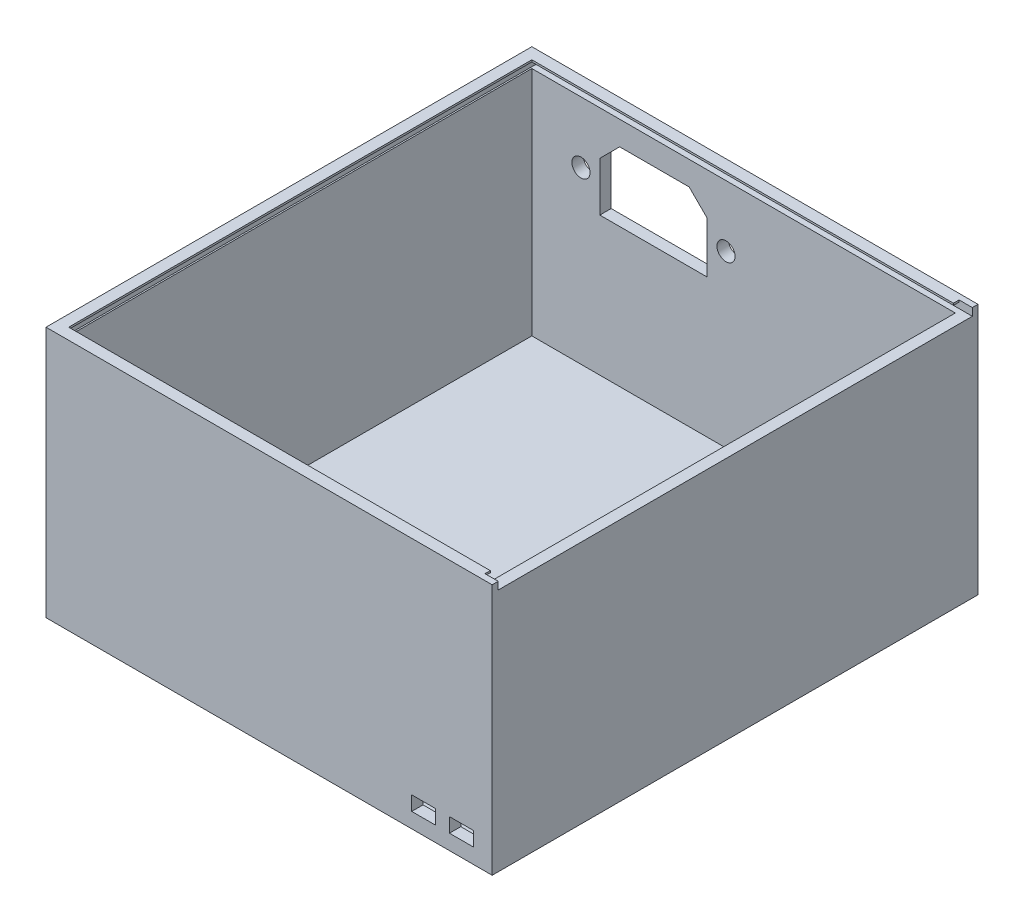
SolidWorks part; units mm, degrees
ref_plane "Front Plane" through (0, 0, 0) normal (0, 0, 1) x (1, 0, 0)
ref_plane "Top Plane" through (0, 0, 0) normal (0, 1, 0) x (1, 0, 0)
ref_plane "Right Plane" through (0, 0, 0) normal (1, 0, 0) x (0, 0, -1)
sketch "Sketch1" plane through (0, 0, 0) normal (0, 1, 0) x (1, 0, 0)
  line L1 (-59.05, 64.3) -> (59.05, 64.3)
  line L2 (-59.05, 64.3) -> (-59.05, -64.3)
  line L3 (-59.05, -64.3) -> (59.05, -64.3)
  line L4 (59.05, 64.3) -> (59.05, -64.3)
  line L5 (-59.05, 64.3) -> (59.05, -64.3) construction
  line L6 (-59.05, -64.3) -> (59.05, 64.3) construction
  point P0 (0, 0)
  dimension "D1" = 118.1
  dimension "D2" = 128.6
extrude "Boss-Extrude2" add sketch "Sketch1" along normal blind 66.6
sketch "Sketch4" plane through (0, 0, 64.3) normal (0, 0, 1) x (1, 0, 0)
  line L0 (59.05, 66.6) -> (59.05, 0) construction
  line L1 (47.75, 4) -> (54.05, 4)
  line L2 (47.75, 4) -> (47.75, 7.8)
  line L3 (47.75, 7.8) -> (54.05, 7.8)
  line L4 (54.05, 4) -> (54.05, 7.8)
  line L5 (-59.05, 0) -> (59.05, 0) construction
  line L7 (37.75, 4) -> (44.05, 4)
  line L8 (37.75, 4) -> (37.75, 7.8)
  line L9 (37.75, 7.8) -> (44.05, 7.8)
  line L10 (44.05, 4) -> (44.05, 7.8)
  point P6 (54.05, 5.9)
  point P13 (44.05, 5.9)
  dimension "D1" = 6.3
  dimension "D2" = 3.8
  dimension "D3" = 5
  dimension "D4" = 4
  dimension "D5" = 6.3
  dimension "D6" = 3.8
  dimension "D7" = 15
  dimension "D8" = 4
sketch "Sketch5" plane through (0, 0, -64.3) normal (0, 0, -1) x (-1, 0, 0)
  line L6 (59.05, 66.6) -> (59.05, 0) construction
  line L9 (13.3156, 57.1826) -> (13.9, 57.1826) construction
  line L10 (9.65, 40) -> (38.05, 40)
  line L11 (9.65, 40) -> (9.65, 53.517)
  line L12 (14.4, 58.267) -> (32.8, 58.267)
  line L13 (38.05, 40) -> (38.05, 53.017)
  line L14 (33.8844, 57.1826) -> (32.8, 57.1826) construction
  line L15 (14.4, 58.267) -> (9.65, 53.517)
  line L16 (32.8, 58.267) -> (38.05, 53.017)
  line L17 (-59.05, 0) -> (59.05, 0) construction
  circle A2 centre (43.05, 48.4) radius 2.4
  circle A3 centre (4.65, 48.4) radius 2.4
  point P2 (23.85, 40)
  dimension "D1" = 40
  dimension "D2" = 13.517
  dimension "D3" = 28.4
  dimension "D4" = 18.267
  dimension "D5" = 45
  dimension "D6" = 5
  dimension "D7" = 8.4
  dimension "D8" = 5
  dimension "D9" = 8.4
  dimension "D10" = 16
  dimension "D11" = 45
extrude "Cut-Extrude2" cut sketch "Sketch5" against normal blind 4
extrude "Cut-Extrude3" cut sketch "Sketch4" against normal blind 4
sketch "Sketch6" plane through (0, 66.6, 0) normal (0, 1, 0) x (1, 0, 0)
  line L8 (56.05, -61.3) -> (56.05, 61.3)
  line L9 (56.05, 61.3) -> (-56.05, 61.3)
  line L10 (-56.05, 61.3) -> (-56.05, -61.3)
  line L11 (-56.05, -61.3) -> (56.05, -61.3)
  line L12 (56.05, -61.3) -> (56.05, 61.3)
  line L13 (56.05, 61.3) -> (-56.05, 61.3)
  line L14 (-56.05, 61.3) -> (-56.05, -61.3)
  line L15 (-56.05, -61.3) -> (56.05, -61.3)
  dimension "D1" = 3
extrude "Cut-Extrude4" cut sketch "Sketch6" against normal blind 63.3
sketch "Sketch9" plane through (59.05, 0, 0) normal (1, 0, 0) x (0, 0, -1)
  line L0 (64.3, 66.6) -> (64.3, 0) construction
  line L1 (-62.7, 64.6) -> (62.8, 64.6)
  line L2 (-62.7, 64.6) -> (-62.7, 66.1)
  line L3 (-62.7, 66.1) -> (62.8, 66.1)
  line L4 (62.8, 64.6) -> (62.8, 66.1)
  line L5 (-64.3, 66.6) -> (64.3, 66.6) construction
  point P4 (62.8, 65.35)
  dimension "D1" = 1.5
  dimension "D2" = 125.5
  dimension "D3" = 1.5
  dimension "D4" = 0.5
extrude "Cut-Extrude7" cut sketch "Sketch9" against normal blind 115.5
sketch "Sketch10" plane through (59.05, 0, 0) normal (1, 0, 0) x (0, 0, -1)
  line L0 (-62.7, 66.1) -> (-62.7, 64.6) construction
  line L1 (-62.7, 65.6) -> (62.8, 65.6)
  line L2 (-62.7, 65.6) -> (-62.7, 66.6)
  line L3 (-62.7, 66.6) -> (62.8, 66.6)
  line L4 (62.8, 65.6) -> (62.8, 66.6)
  line L5 (-64.3, 66.6) -> (64.3, 66.6) construction
  point P4 (-62.7, 66.1)
  dimension "D1" = 125.5
  dimension "D2" = 0.5
  dimension "D3" = 0
  dimension "D4" = 0
extrude "Cut-Extrude8" cut sketch "Sketch10" against normal blind 3.5
